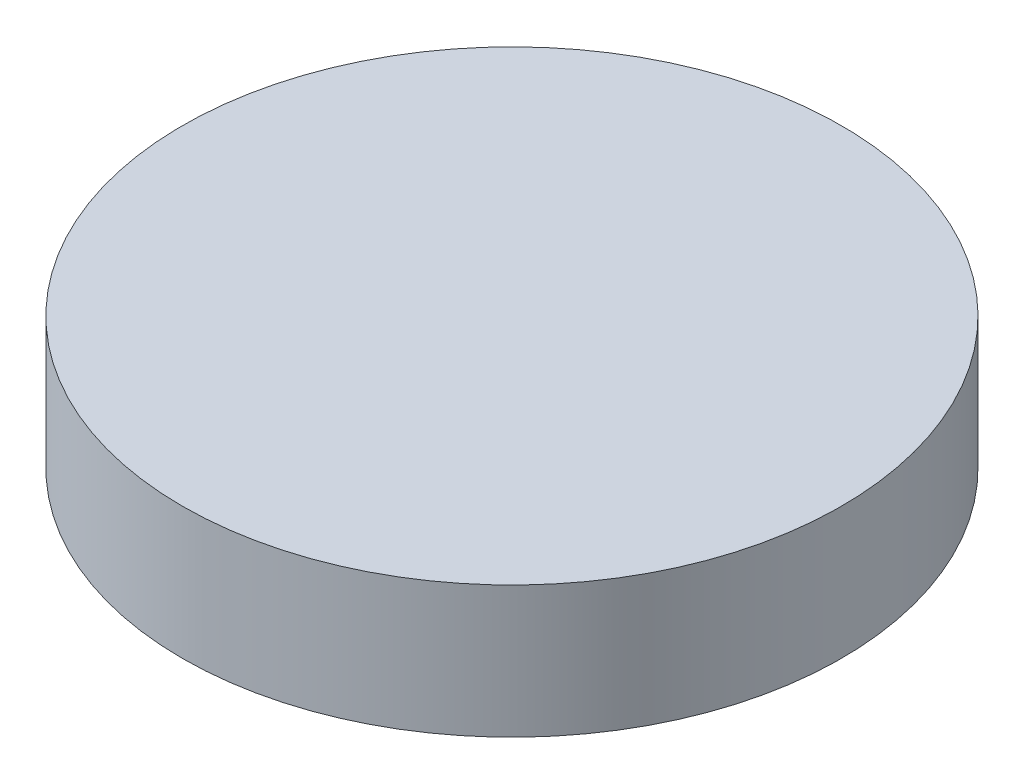
SolidWorks part; units mm, degrees
ref_plane "Front Plane" through (0, 0, 0) normal (0, 0, 1) x (1, 0, 0)
ref_plane "Top Plane" through (0, 0, 0) normal (0, 1, 0) x (1, 0, 0)
ref_plane "Right Plane" through (0, 0, 0) normal (1, 0, 0) x (0, 0, -1)
sketch "Sketch1" plane through (0, 0, 0) normal (0, 1, 0) x (1, 0, 0)
  circle A0 centre (0, 0) radius 10
extrude "Boss-Extrude1" add sketch "Sketch1" along normal blind 3
sketch "Sketch2" plane through (0, 3, 0) normal (0, 1, 0) x (1, 0, 0)
  line L1 (2.9587, -2.753) -> (3.8636, 1.1858)
  line L2 (3.8636, 1.1858) -> (0.9048, 3.9389)
  line L3 (0.9048, 3.9389) -> (-2.9587, 2.753)
  line L4 (-2.9587, 2.753) -> (-3.8636, -1.1858)
  line L5 (-3.8636, -1.1858) -> (-0.9048, -3.9389)
  line L6 (-0.9048, -3.9389) -> (2.9587, -2.753)
  circle A0 centre (0, 0) radius 3.5 construction
  dimension "D1" = 7
extrude "Cut-Extrude2" cut sketch "Sketch2" against normal through all
sketch "Sketch3" plane through (0, 3, 0) normal (0, 1, 0) x (1, 0, 0)
  circle A0 centre (0, 0) radius 10
extrude "Boss-Extrude2" add sketch "Sketch3" along normal blind 1
